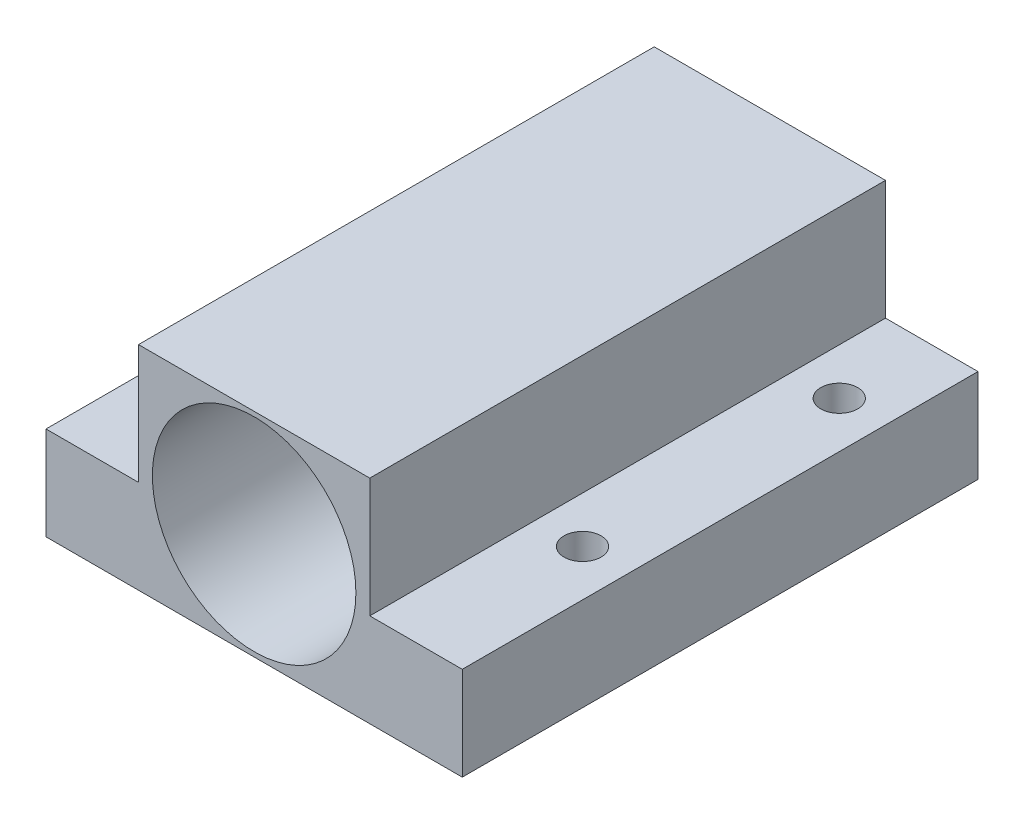
SolidWorks part; units mm, degrees
material "ABS"
ref_plane "Front Plane" through (0, 0, 0) normal (0, 0, 1) x (1, 0, 0)
ref_plane "Top Plane" through (0, 0, 0) normal (0, 1, 0) x (1, 0, 0)
ref_plane "Right Plane" through (0, 0, 0) normal (1, 0, 0) x (0, 0, -1)
sketch "Sketch1" plane through (0, 0, 0) normal (0, 0, 1) x (1, 0, 0)
  line L0 (-65.4098, -16.7) -> (184.5902, -16.7) construction
  line L1 (-12.5, 6.3) -> (12.5, 6.3)
  line L2 (-12.5, 6.3) -> (-12.5, -16.7)
  line L3 (-12.5, -16.7) -> (12.5, -16.7)
  line L4 (12.5, 6.3) -> (12.5, -16.7)
  line L5 (-12.5, 6.3) -> (12.5, -16.7) construction
  line L6 (-12.5, -16.7) -> (12.5, 6.3) construction
  line L7 (12.5, -16.7) -> (22.5, -16.7)
  line L8 (12.5, -16.7) -> (12.5, -6.6)
  line L9 (12.5, -6.6) -> (22.5, -6.6)
  line L10 (22.5, -16.7) -> (22.5, -6.6)
  line L11 (12.5, -16.7) -> (22.5, -6.6) construction
  line L12 (12.5, -6.6) -> (22.5, -16.7) construction
  line L13 (-12.5, -16.7) -> (-22.5, -16.7)
  line L14 (-12.5, -16.7) -> (-12.5, -6.6)
  line L15 (-12.5, -6.6) -> (-22.5, -6.6)
  line L16 (-22.5, -16.7) -> (-22.5, -6.6)
  line L17 (-12.5, -16.7) -> (-22.5, -6.6) construction
  line L18 (-12.5, -6.6) -> (-22.5, -16.7) construction
  circle A0 centre (0, -5.2) radius 4.1
  circle A1 centre (0, -5.2) radius 11
  point P8 (0, -5.2)
  point P14 (17.5, -11.65)
  point P16 (-17.5, -11.65)
  dimension "D4" = 8.2
  dimension "D5" = 22
  dimension "D11" = 11.5
  dimension "D2" = 0
  dimension "D3" = 25
  dimension "D6" = 10
  dimension "D8" = 10
  dimension "D9" = 10.1
  dimension "D10" = 12.5
  dimension "D12" = 11.5
  dimension "D13" = 5.2
extrude "Boss-Extrude1" add sketch "Sketch1" along normal up to surface (55.75 mm away) contours L4 L1 L2 L3 A1 | L16 L13 L2 L15 | L7 L10 L9 L4
sketch "Sketch2" plane through (0, -6.6, 0) normal (0, 1, 0) x (1, 0, 0)
  line L0 (-22.5, 0) -> (-12.5, -55.75)
  line L1 (-12.5, -55.75) -> (-22.5, -55.75)
  line L2 (-22.5, -55.75) -> (-12.5, 0)
  line L3 (12.5, 0) -> (22.5, -55.75)
  line L4 (22.5, -55.75) -> (22.5, 0)
  line L5 (22.5, 0) -> (12.5, -55.75)
  circle A0 centre (-17.5, -10) radius 2
  circle A1 centre (17.5, -10) radius 2
  circle A2 centre (17.5, -10) radius 2 construction
  circle A3 centre (-17.5, -10) radius 2 construction
  circle A4 centre (-17.5, -37.75) radius 2
  circle A5 centre (17.5, -37.75) radius 2
  circle A6 centre (17.5, -37.75) radius 2 construction
  circle A7 centre (-17.5, -37.75) radius 2 construction
  dimension "D1" = 4
  dimension "D2" = 4
extrude "Cut-Extrude1" cut sketch "Sketch2" against normal through all contours A0 | A4 | A1 | A5
